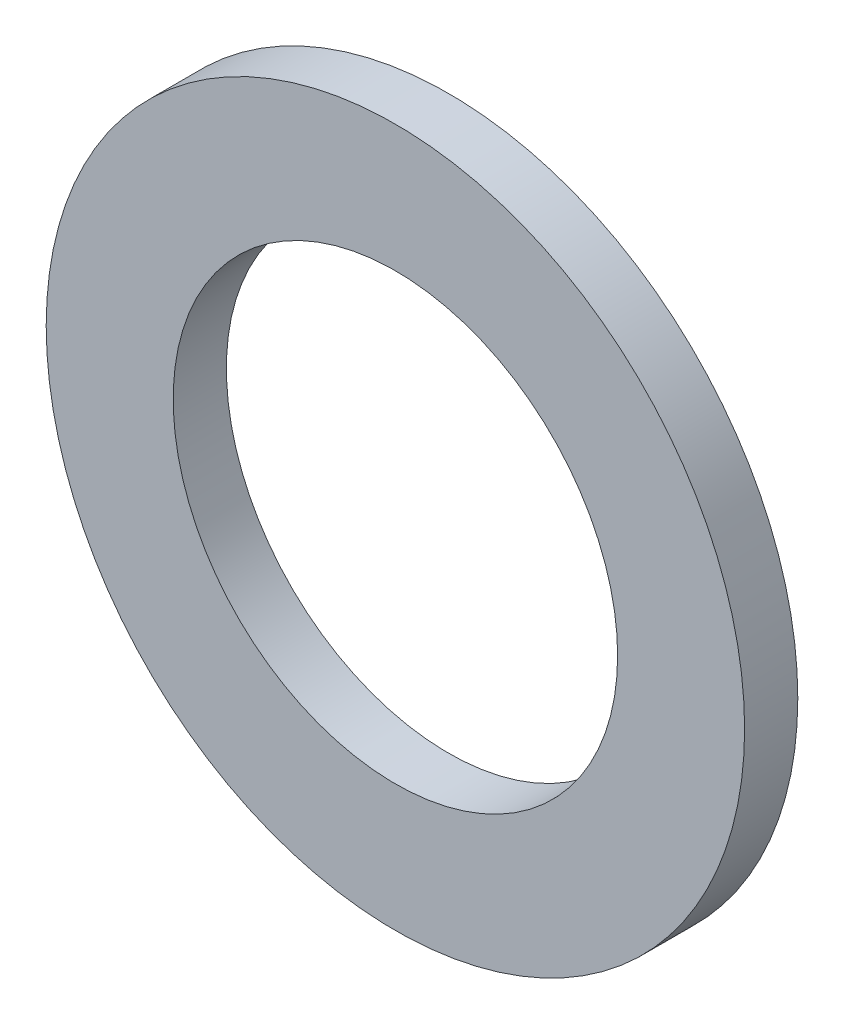
SolidWorks part; units mm, degrees
ref_plane "Front Plane" through (0, 0, 0) normal (0, 0, 1) x (1, 0, 0)
ref_plane "Top Plane" through (0, 0, 0) normal (0, 1, 0) x (1, 0, 0)
ref_plane "Right Plane" through (0, 0, 0) normal (1, 0, 0) x (0, 0, -1)
sketch "Sketch1" plane through (0, 0, 0) normal (0, 0, 1) x (1, 0, 0)
  circle A0 centre (0, 0) radius 14
  dimension "D1" = 28
extrude "Extrude-Thin1" add sketch "Sketch1" along normal blind 3.35 thin
scale "Scale1" scale about centroid uniform scaling yes scale factor 0.8
